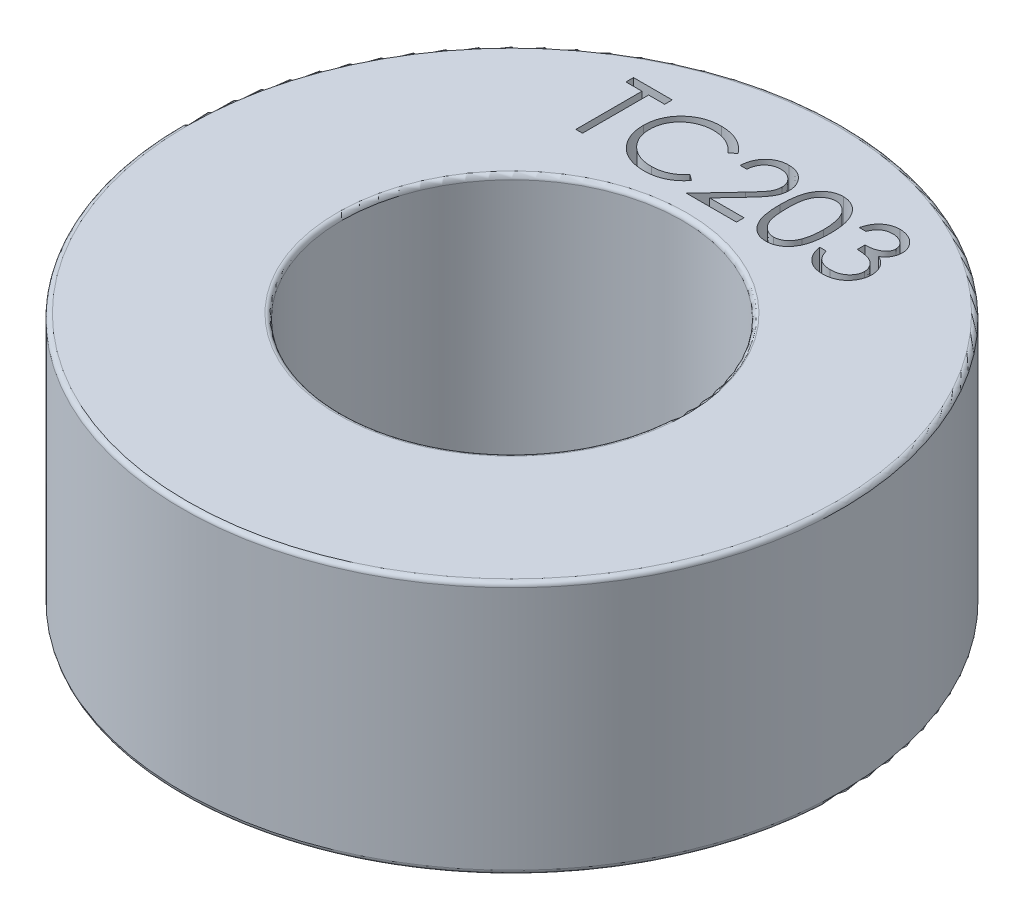
SolidWorks part; units mm, degrees
ref_plane "Front Plane" through (0, 0, 0) normal (0, 0, 1) x (1, 0, 0)
ref_plane "Top Plane" through (0, 0, 0) normal (0, 1, 0) x (1, 0, 0)
ref_plane "Right Plane" through (0, 0, 0) normal (1, 0, 0) x (0, 0, -1)
sketch "Toroidal Core TC229" plane through (0, 0, 0) normal (0, 0, 1) x (1, 0, 0)
  line L0 (0, -8.108) -> (0, 13.3131) construction
  line L2 (5.6461, 0) -> (10.5039, 0)
  line L3 (5.5, 0.1461) -> (5.5, 8.0539)
  line L4 (5.6461, 8.2) -> (10.5039, 8.2)
  line L5 (10.65, 0.1461) -> (10.65, 8.0539)
  arc A0 (5.6461, 0) -> (5.5, 0.1461) centre (5.6461, 0.1461) cw
  arc A1 (10.5039, 0) -> (10.65, 0.1461) centre (10.5039, 0.1461) ccw
  arc A2 (10.5039, 8.2) -> (10.65, 8.0539) centre (10.5039, 8.0539) cw
  arc A3 (5.5, 8.0539) -> (5.6461, 8.2) centre (5.6461, 8.0539) cw
  point P9 (5.5, 0)
  point P12 (10.65, 0)
  point P15 (10.65, 8.2)
  point P18 (5.5, 8.2)
  dimension "D4" = 0.1461
  dimension "D1" = 5.15
  dimension "D2" = 8.2
  dimension "D3" = 5.5
revolve "Revolve2" add sketch "Toroidal Core TC229" angle 360 about L0
sketch "Sketch1" plane through (0, 8.2, 0) normal (0, 1, 0) x (1, 0, 0)
  text T0 "TC203\r\n" font "Century Gothic" height in points 9
extrude "Cut-Extrude1" cut sketch "Sketch1" against normal blind 1
